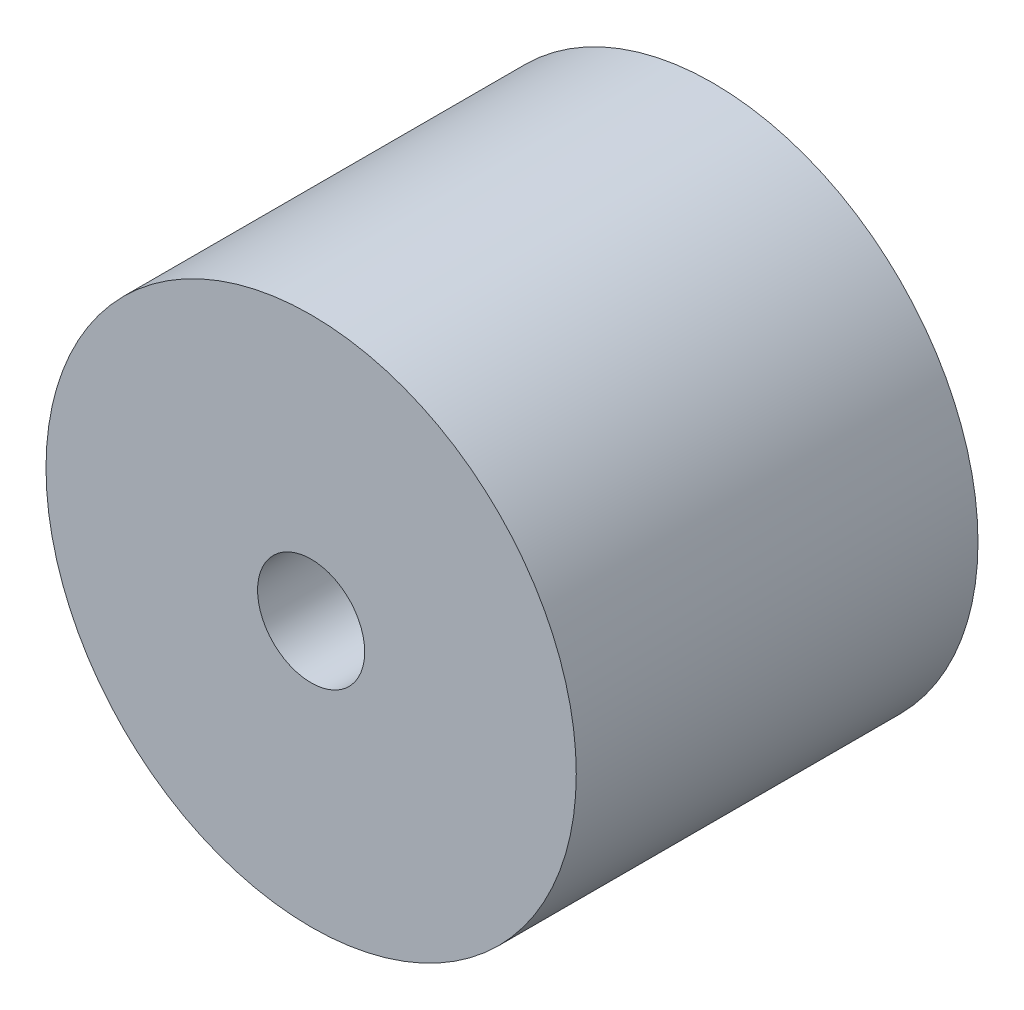
SolidWorks part; units mm, degrees
ref_plane "前视基准面" through (0, 0, 0) normal (0, 0, 1) x (1, 0, 0)
ref_plane "上视基准面" through (0, 0, 0) normal (0, 1, 0) x (1, 0, 0)
ref_plane "右视基准面" through (0, 0, 0) normal (1, 0, 0) x (0, 0, -1)
sketch "草图1" plane through (0, 0, 0) normal (0, 0, 1) x (1, 0, 0)
  circle A0 centre (0, 0) radius 9.9
  circle A1 centre (0, 0) radius 2
extrude "凸台-拉伸1" add sketch "草图1" along normal blind 15
